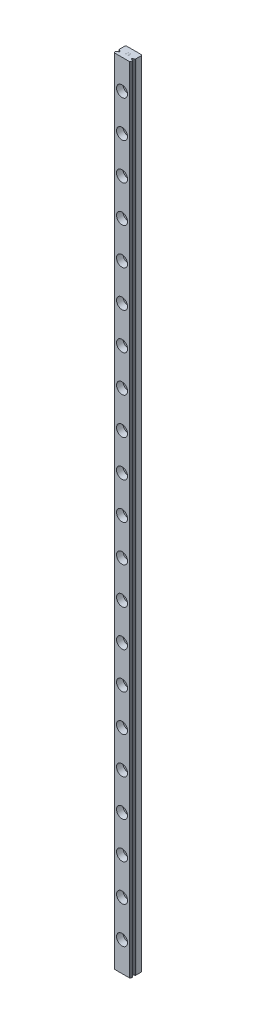
SolidWorks part; units mm, degrees
material "acero"
ref_plane "Alzado" through (0, 0, 0) normal (0, 0, 1) x (1, 0, 0)
ref_plane "Planta" through (0, 0, 0) normal (0, 1, 0) x (1, 0, 0)
ref_plane "Vista lateral" through (0, 0, 0) normal (1, 0, 0) x (0, 0, -1)
ref_plane "Plano1" through (0, 0, 0) normal (0, -1, 0) x (1, 0, 0)
sketch "Croquis1" plane through (0, 0, 0) normal (0, -1, 0) x (1, 0, 0)
  line L0 (4.5, 0) -> (4.5, 6.0117)
  line L1 (4.5, 6.0117) -> (4.1, 6.5)
  line L2 (4.1, 6.5) -> (-4.1, 6.5)
  line L3 (-4.1, 6.5) -> (-4.5, 6.0117)
  line L4 (-4.5, 6.0117) -> (-4.5, 0)
  line L5 (-4.5, 0) -> (4.5, 0)
extrude "Saliente-Extruir1" add sketch "Croquis1" against normal blind 432
sketch "Croquis2" plane through (0, 432, 0) normal (0, 1, 0) x (-1, 0, 0)
  line L0 (-4.5, 4.8802) -> (-4.5, 4.0315)
  line L1 (-4.5, 4.0315) -> (-3.8193, 4.0315)
  line L2 (-3.8193, 4.8802) -> (-4.5, 4.8802)
  arc A1 (-3.8193, 4.0315) -> (-3.8193, 4.8802) centre (-3.6695, 4.4558) ccw
  dimension "D4" = 0.9
  dimension "D2" = 0.8487
extrude "Cortar-Extruir1" cut sketch "Croquis2" against normal through all
sketch "Croquis3" plane through (0, 432, 0) normal (0, 1, 0) x (-1, 0, 0)
  line L0 (-4.0265, 4.0315) -> (-4.5, 4.0315)
  line L1 (-4.5, 4.0315) -> (-4.5, 3.5836)
  arc A0 (-4.5, 3.5836) -> (-4.0265, 4.0315) centre (-4.8765, 4.4558) ccw
extrude "Cortar-Extruir2" cut sketch "Croquis3" against normal through all
sketch "Croquis4" plane through (0, 432, 0) normal (0, 1, 0) x (-1, 0, 0)
  line L0 (-4.5, 5.3281) -> (-4.5, 4.8802)
  line L1 (-4.5, 4.8802) -> (-4.0265, 4.8802)
  arc A0 (-4.0265, 4.8802) -> (-4.5, 5.3281) centre (-4.8765, 4.4558) ccw
extrude "Cortar-Extruir3" cut sketch "Croquis4" against normal through all
sketch "Croquis5" plane through (0, 432, 0) normal (0, 1, 0) x (-1, 0, 0)
  line L0 (4.5, 4.0315) -> (4.5, 4.8802)
  line L1 (4.5, 4.8802) -> (3.8193, 4.8802)
  line L2 (3.8193, 4.0315) -> (4.5, 4.0315)
  arc A1 (3.8193, 4.8802) -> (3.8193, 4.0315) centre (3.6695, 4.4558) ccw
  dimension "D3" = 0.9
  dimension "D2" = 0.8487
extrude "Cortar-Extruir4" cut sketch "Croquis5" against normal through all
sketch "Croquis6" plane through (0, 432, 0) normal (0, 1, 0) x (-1, 0, 0)
  line L0 (4.0265, 4.8802) -> (4.5, 4.8802)
  line L1 (4.5, 4.8802) -> (4.5, 5.3281)
  arc A0 (4.5, 5.3281) -> (4.0265, 4.8802) centre (4.8765, 4.4558) ccw
extrude "Cortar-Extruir5" cut sketch "Croquis6" against normal through all
sketch "Croquis7" plane through (0, 432, 0) normal (0, 1, 0) x (-1, 0, 0)
  line L0 (4.5, 3.5836) -> (4.5, 4.0315)
  line L1 (4.5, 4.0315) -> (4.0265, 4.0315)
  arc A0 (4.0265, 4.0315) -> (4.5, 3.5836) centre (4.8765, 4.4558) ccw
extrude "Cortar-Extruir6" cut sketch "Croquis7" against normal through all
sketch "Croquis8" plane through (0, 432, 0) normal (0, 1, 0) x (-1, 0, 0)
  line L0 (0.8914, 3.4037) -> (0.7147, 3.1682)
  line L1 (0.7147, 3.1682) -> (0.2187, 2.611)
  line L2 (0.2187, 2.611) -> (1.0946, 2.6111)
  line L3 (1.0946, 2.6111) -> (1.0946, 2.696)
  line L4 (1.0946, 2.696) -> (0.3987, 2.696)
  line L5 (0.3987, 2.696) -> (0.7943, 3.1495)
  line L6 (0.7943, 3.1495) -> (0.9743, 3.3891)
  line L7 (0.9743, 3.3891) -> (1.0671, 3.5734)
  line L8 (1.0671, 3.5734) -> (0.9541, 3.8023)
  line L9 (0.9541, 3.8023) -> (0.7877, 3.8851)
  line L10 (0.7877, 3.8851) -> (0.543, 3.8851)
  line L11 (0.543, 3.8851) -> (0.3754, 3.8036)
  line L12 (0.3754, 3.8036) -> (0.295, 3.6384)
  line L13 (0.295, 3.6384) -> (0.295, 3.562)
  line L14 (0.295, 3.562) -> (0.3813, 3.562)
  line L15 (0.3813, 3.562) -> (0.3813, 3.6318)
  line L16 (0.3813, 3.6318) -> (0.4377, 3.7436)
  line L17 (0.4377, 3.7436) -> (0.5496, 3.8001)
  line L18 (0.5496, 3.8001) -> (0.7802, 3.8001)
  line L19 (0.7802, 3.8001) -> (0.893, 3.7438)
  line L20 (0.893, 3.7438) -> (0.9762, 3.576)
  line L21 (0.9762, 3.576) -> (0.8914, 3.4037)
extrude "Cortar-Extruir7" cut sketch "Croquis8" against normal blind 0.0022
sketch "Croquis9" plane through (0, 0, 0) normal (0, -1, 0) x (1, 0, 0)
  line L0 (-0.2146, 3.8851) -> (-0.954, 3.8851)
  line L1 (-0.954, 3.8851) -> (-0.954, 2.6111)
  line L2 (-0.954, 2.6111) -> (-0.2146, 2.6111)
  line L3 (-0.2146, 2.6111) -> (-0.2146, 2.696)
  line L4 (-0.2146, 2.696) -> (-0.869, 2.696)
  line L5 (-0.869, 2.696) -> (-0.869, 3.2056)
  line L6 (-0.869, 3.2056) -> (-0.5124, 3.2056)
  line L7 (-0.5124, 3.2056) -> (-0.5124, 3.2905)
  line L8 (-0.5124, 3.2905) -> (-0.869, 3.2905)
  line L9 (-0.869, 3.2905) -> (-0.869, 3.8001)
  line L10 (-0.869, 3.8001) -> (-0.2146, 3.8001)
  line L11 (-0.2146, 3.8001) -> (-0.2146, 3.8851)
extrude "Cortar-Extruir8" cut sketch "Croquis9" against normal blind 0.0022
sketch "Croquis10" plane through (0, 432, 0) normal (0, 1, 0) x (-1, 0, 0)
  line L0 (-0.2146, 3.8851) -> (-0.954, 3.8851)
  line L1 (-0.954, 3.8851) -> (-0.954, 2.6111)
  line L2 (-0.954, 2.6111) -> (-0.2146, 2.6111)
  line L3 (-0.2146, 2.6111) -> (-0.2146, 2.696)
  line L4 (-0.2146, 2.696) -> (-0.869, 2.696)
  line L5 (-0.869, 2.696) -> (-0.869, 3.2056)
  line L6 (-0.869, 3.2056) -> (-0.5124, 3.2056)
  line L7 (-0.5124, 3.2056) -> (-0.5124, 3.2905)
  line L8 (-0.5124, 3.2905) -> (-0.869, 3.2905)
  line L9 (-0.869, 3.2905) -> (-0.869, 3.8001)
  line L10 (-0.869, 3.8001) -> (-0.2146, 3.8001)
  line L11 (-0.2146, 3.8001) -> (-0.2146, 3.8851)
extrude "Cortar-Extruir9" cut sketch "Croquis10" against normal blind 0.0022
sketch "Croquis11" plane through (0, 0, 0) normal (0, -1, 0) x (1, 0, 0)
  line L0 (0.5101, 3.6208) -> (0.6071, 3.7187)
  line L1 (0.6071, 3.7187) -> (0.6071, 2.6094)
  line L2 (0.6071, 2.6094) -> (0.692, 2.6094)
  line L3 (0.692, 2.6094) -> (0.692, 3.8834)
  line L4 (0.692, 3.8834) -> (0.6741, 3.8834)
  line L5 (0.6741, 3.8834) -> (0.6741, 3.7951)
  line L6 (0.6741, 3.7951) -> (0.3691, 3.6407)
  line L7 (0.3691, 3.6407) -> (0.3691, 3.5513)
  line L8 (0.3691, 3.5513) -> (0.5101, 3.6208)
extrude "Cortar-Extruir10" cut sketch "Croquis11" against normal blind 0.0022
draft "Ángulo de salida1" type of draft neutral plane draft angle 45.147 faces to draft 1 face at (0.6741, 0.0011, 3.8392) neutral plane through (0.692, 0.0022, 3.8834) neutral plane normal (0, 0, -1) parameters "D1"=45.147
chamfer "Chaflán1" distance 0.4 angle 45 2 edges at (4.5, 216, 0) (-4.5, 216, 0)
fillet "Redondeo1" radius 0.13 8 edges at (4.5, 216, 3.5836) (4.0265, 216, 4.0315) (-4.0265, 216, 4.0315) (-4.0265, 216, 4.8802) (-4.5, 216, 5.3281) (-4.5, 216, 3.5836) (4.5, 216, 5.3281) (4.0265, 216, 4.8802)
hole_wizard "Taladro roscado M3.5x0.61" positions "Croquis35" profile "Croquis34" tap size "M3.5x0.6" standard "Ansi Metric"
sketch "Croquis35" plane through (0, 0, 0) normal (0, 0, -1) x (-1, 0, 0)
  line L3 (0, -8.7858) -> (0, 432) construction
  line L5 (-4.1, 432) -> (4.1, 432) construction
  line L6 (-4.1, 0) -> (4.1, 0) construction
  point P39 (0, 16)
  dimension "D1" = 16
sketch "Croquis34" plane through (0, 16, 0) normal (1, 0, 0) x (0, 1, 0)
  line L0 (0, 0) -> (0, 8)
  line L1 (0, 8) -> (3, 8)
  line L2 (3, 8) -> (3, 3)
  line L3 (3, 3) -> (1.75, 3)
  line L4 (1.75, 3) -> (1.75, 0)
  line L5 (1.75, 0) -> (0, 0)
  line L10 (0, 8) -> (-3, 8) construction
  line L11 (0, -6.35) -> (0, 107.95) construction
  dimension "Diámetro de perforador para roscar" = 6
  dimension "Profundidad de perforador para roscar" = 8
  dimension "Diámetro mayor de rosca" = 3.5
  dimension "Profundidad de rosca" = 3
  dimension "Ángulo de perforador" = 180
pattern_linear "MatrizL2" count 21 spacing 20 along (0, 1, 0) of "Taladro roscado M3.5x0.61"
